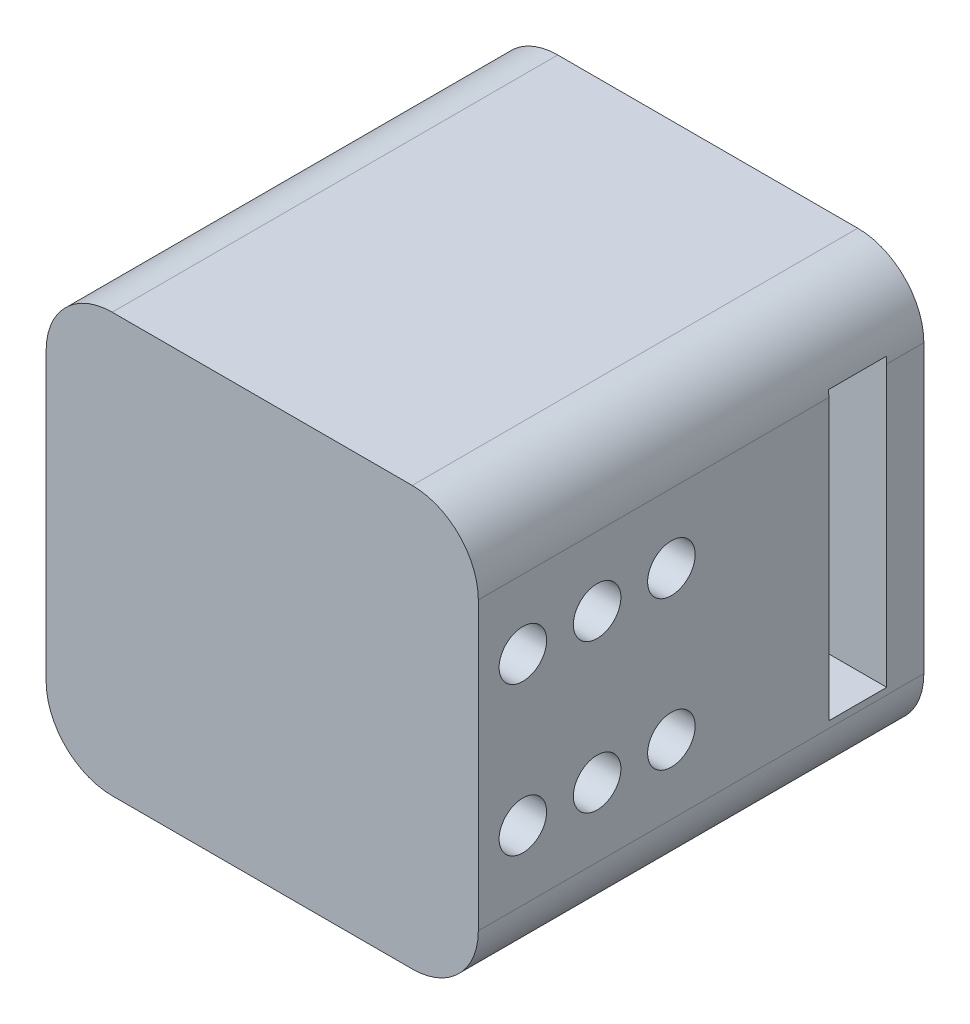
SolidWorks part; units mm, degrees
material "6061-O (SS)"
ref_plane "前视基准面" through (0, 0, 0) normal (0, 0, 1) x (1, 0, 0)
ref_plane "上视基准面" through (0, 0, 0) normal (0, 1, 0) x (1, 0, 0)
ref_plane "右视基准面" through (0, 0, 0) normal (1, 0, 0) x (0, 0, -1)
other "Configuration Table"
sketch "草图1" plane through (0, 0, 0) normal (0, 0, 1) x (1, 0, 0)
  line L1 (-10.1, 14.1) -> (10.1, 14.1)
  line L2 (-14.55, 9.65) -> (-14.55, -9.65)
  line L3 (-10.1, -14.1) -> (10.1, -14.1)
  line L4 (14.55, 9.65) -> (14.55, -9.65)
  line L5 (-14.55, 14.1) -> (14.55, -14.1) construction
  line L6 (-14.55, -14.1) -> (14.55, 14.1) construction
  arc A0 (10.1, 14.1) -> (14.55, 9.65) centre (10.1, 9.65) cw
  arc A1 (10.1, -14.1) -> (14.55, -9.65) centre (10.1, -9.65) ccw
  arc A2 (-14.55, -9.65) -> (-10.1, -14.1) centre (-10.1, -9.65) ccw
  arc A3 (-10.1, 14.1) -> (-14.55, 9.65) centre (-10.1, 9.65) ccw
  point P0 (0, 0)
  dimension "D2" = 4.45
  dimension "D1" = 29.1
  dimension "D3" = 28.2
extrude "凸台-拉伸1" add sketch "草图1" along normal blind 30
sketch "草图2" plane through (14.55, 0, 0) normal (1, 0, 0) x (0, 0, -1)
  line L0 (0, 0) -> (50000, 0) construction
  line L1 (-27, -5) -> (-22, -5) construction
  line L2 (-27, -5) -> (-27, 5) construction
  line L3 (-30, -9.65) -> (-30, 9.65) construction
  circle A0 centre (-27, -5) radius 1.6
  circle A1 centre (-22, -5) radius 1.6
  circle A2 centre (-17, -5) radius 1.6
  circle A3 centre (-22, 5) radius 1.6
  circle A4 centre (-17, 5) radius 1.6
  circle A5 centre (-27, 5) radius 1.6
  dimension "D5" = 3.2
  dimension "D2" = 5
  dimension "D3" = 10
  dimension "D6" = 3
  dimension "D1" = 3
  dimension "D4" = 2
extrude "切除-拉伸1" cut sketch "草图2" against normal blind 3.2
mirror "镜向1" about plane through (0, 0, 0) normal (1, 0, 0) of "切除-拉伸1"
sketch "草图4" plane through (14.55, 0, 0) normal (1, 0, 0) x (0, 0, -1)
  line L0 (-25, 0.45) -> (-50025, 0.45) construction
  line L2 (0, -9.65) -> (0, 9.65) construction
  line L3 (-6.4, 10.1) -> (-2.5, 10.1)
  line L4 (-6.4, 10.1) -> (-6.4, -9.2)
  line L5 (-6.4, -9.2) -> (-2.5, -9.2)
  line L6 (-2.5, 10.1) -> (-2.5, -9.2)
  line L7 (-6.4, 10.1) -> (-2.5, -9.2) construction
  line L8 (-6.4, -9.2) -> (-2.5, 10.1) construction
  line L9 (-30, -9.65) -> (0, -9.65) construction
  point P5 (-4.45, 0.45)
  dimension "D1" = 19.3
  dimension "D2" = 3.9
  dimension "D3" = 2.5
  dimension "D4" = 10.1
extrude "切除-拉伸2" cut sketch "草图4" against normal blind 23
sketch "草图5" plane through (-14.55, 0, 0) normal (-1, 0, 0) x (0, 0, 1)
  line L0 (0, 0.45) -> (50000, 0.45) construction
  line L1 (0, 9.65) -> (0, -9.65) construction
  line L2 (8.4, 10.1) -> (12.3, 10.1)
  line L3 (8.4, 10.1) -> (8.4, -9.2)
  line L4 (8.4, -9.2) -> (12.3, -9.2)
  line L5 (12.3, 10.1) -> (12.3, -9.2)
  line L6 (8.4, 10.1) -> (12.3, -9.2) construction
  line L7 (8.4, -9.2) -> (12.3, 10.1) construction
  line L8 (30, -9.65) -> (0, -9.65) construction
  point P3 (10.35, 0.45)
  dimension "D1" = 8.4
  dimension "D2" = 3.9
  dimension "D3" = 19.3
  dimension "D4" = 10.1
extrude "切除-拉伸3" cut sketch "草图5" against normal blind 23
sketch "草图6" plane through (0, 0, 0) normal (0, 0, -1) x (-1, 0, 0)
  line L0 (0, 0) -> (0, -50000) construction
  line L1 (10.1, -14.1) -> (-10.1, -14.1) construction
  line L2 (-3.45, -9.2) -> (3.45, -9.2)
  line L3 (-3.45, -9.2) -> (-3.45, -14.1)
  line L4 (-3.45, -14.1) -> (3.45, -14.1)
  line L5 (3.45, -9.2) -> (3.45, -14.1)
  line L6 (-3.45, -9.2) -> (3.45, -14.1) construction
  line L7 (-3.45, -14.1) -> (3.45, -9.2) construction
  point P3 (0, -11.65)
  dimension "D1" = 6.9
  dimension "D2" = 4.9
extrude "切除-拉伸4" cut sketch "草图6" against normal blind 20
